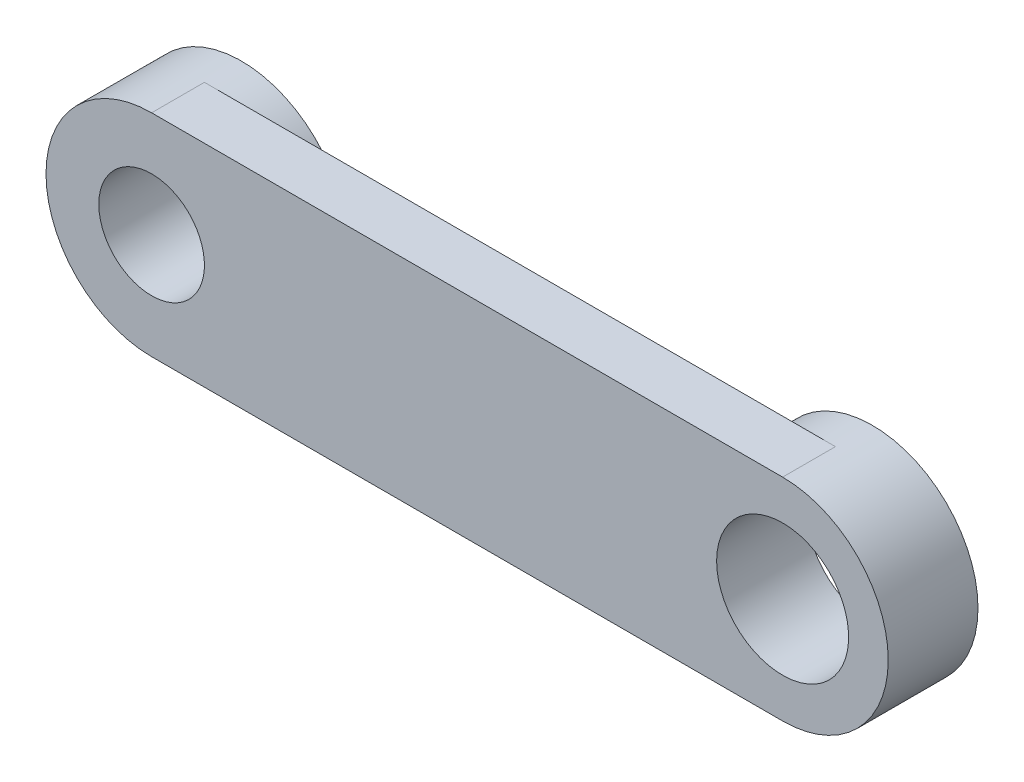
SolidWorks part; units mm, degrees
ref_plane "Piano frontale" through (0, 0, 0) normal (0, 0, 1) x (1, 0, 0)
ref_plane "Piano superiore" through (0, 0, 0) normal (0, 1, 0) x (1, 0, 0)
ref_plane "Piano destro" through (0, 0, 0) normal (1, 0, 0) x (0, 0, -1)
sketch "Schizzo1" plane through (0, 0, 0) normal (0, 0, 1) x (1, 0, 0)
  line L1 (59.75, -20) -> (-59.75, -20)
  line L2 (59.75, -20) -> (59.75, 20)
  line L3 (59.75, 20) -> (-59.75, 20)
  line L4 (-59.75, -20) -> (-59.75, 20)
  line L5 (59.75, -20) -> (-59.75, 20) construction
  line L6 (59.75, 20) -> (-59.75, -20) construction
  point P0 (0, 0)
  dimension "D1" = 119.5
  dimension "D2" = 40
extrude "Estrusione-Estrusione1" add sketch "Schizzo1" along normal blind 10
sketch "Schizzo2" plane through (0, 0, 10) normal (0, 0, 1) x (1, 0, 0)
  line L0 (-59.75, 0) -> (59.75, 0) construction
  line L1 (-59.75, 20) -> (-59.75, -20) construction
  line L2 (59.75, -20) -> (59.75, 20) construction
  circle A0 centre (-59.75, 0) radius 20
  circle A2 centre (59.75, 0) radius 20
  dimension "D1" = 40
  dimension "D3" = 40
extrude "Estrusione-Estrusione2" add sketch "Schizzo2" against normal blind 17
sketch "Schizzo3" plane through (0, 0, -7) normal (0, 0, -1) x (-1, 0, 0)
  circle A0 centre (-59.75, 0) radius 12.5
  circle A1 centre (59.75, 0) radius 10
  circle A2 centre (59.75, 0) radius 20 construction
  circle A3 centre (-59.75, 0) radius 20 construction
  dimension "D1" = 25
  dimension "D2" = 20
extrude "Taglio-Estrusione1" cut sketch "Schizzo3" against normal through all
